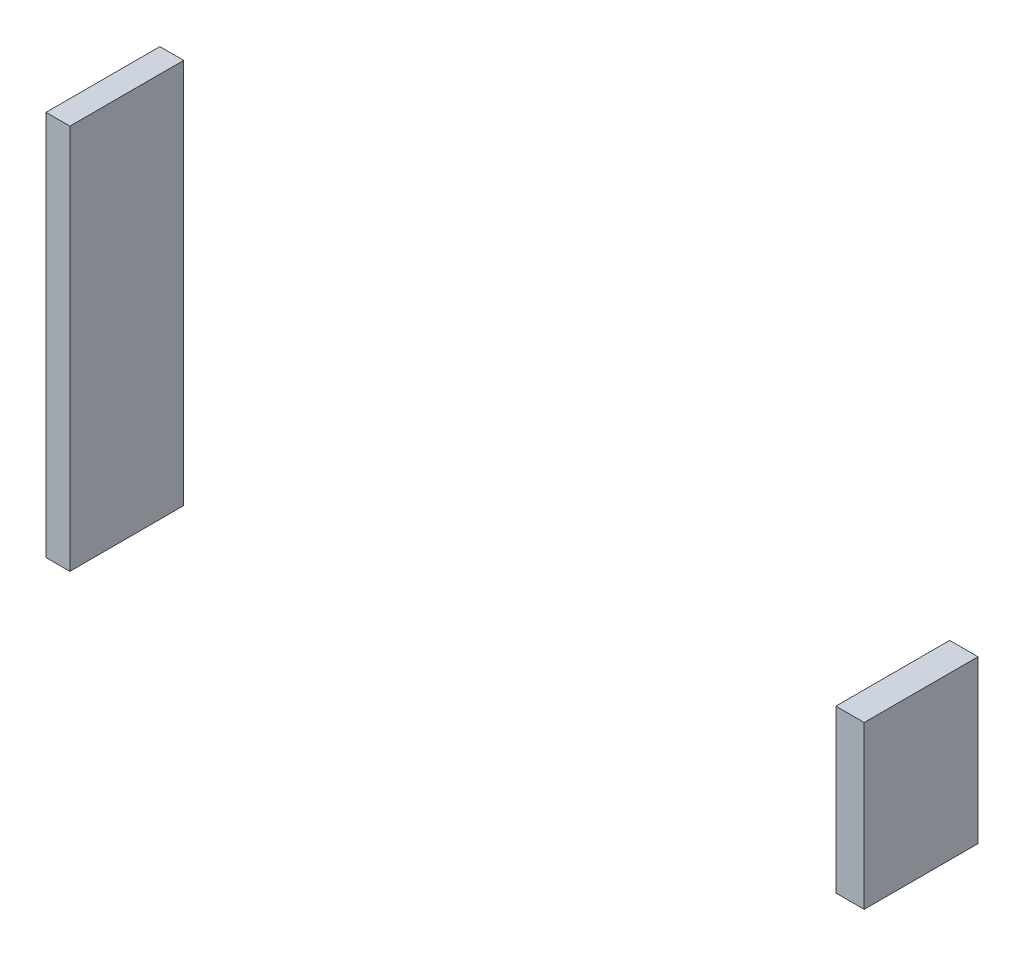
SolidWorks part; units mm, degrees
other "Markup1"
sketch "Sketch2" plane through (37.356, 18.4716, 0) normal (0.2313, 0.9589, -0.1644) x (0.9715, -0.2366, -0.0132)
ref_plane "Front Plane" through (0, 0, 0) normal (0, 0, 1) x (1, 0, 0)
ref_plane "Top Plane" through (0, 0, 0) normal (0, 1, 0) x (1, 0, 0)
ref_plane "Right Plane" through (0, 0, 0) normal (1, 0, 0) x (0, 0, -1)
sketch "Sketch1" plane through (0, 0, 0) normal (0, 0, 1) x (1, 0, 0)
  line L1 (-35.9113, -17.0957) -> (-38.1128, -17.0957)
  line L2 (-35.9113, -17.0957) -> (-35.9113, 18.4716)
  line L3 (-35.9113, 18.4716) -> (-38.1128, 18.4716)
  line L4 (-38.1128, -17.0957) -> (-38.1128, 18.4716)
  line L5 (34.7418, 7.4643) -> (37.356, 7.4643)
  line L6 (34.7418, 7.4643) -> (34.7418, -7.4643)
  line L7 (34.7418, -7.4643) -> (37.356, -7.4643)
  line L8 (37.356, 7.4643) -> (37.356, -7.4643)
  line L9 (34.7418, 7.4643) -> (37.356, -7.4643) construction
  line L10 (34.7418, -7.4643) -> (37.356, 7.4643) construction
  point P4 (36.0489, 0)
extrude "Boss-Extrude1" add sketch "Sketch1" along normal blind 10.5
